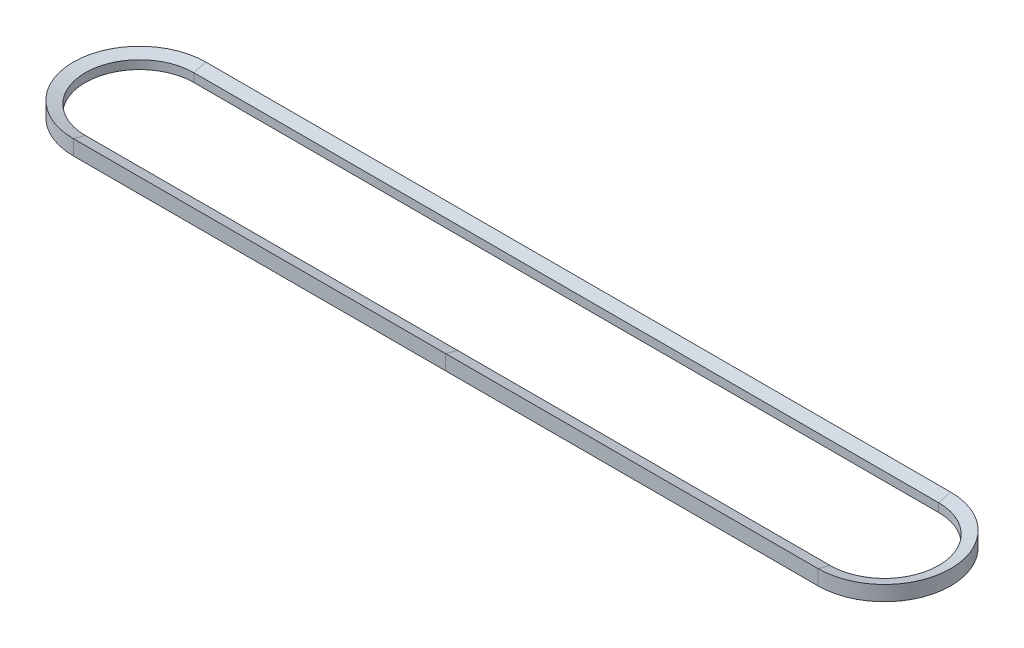
SolidWorks part; units mm, degrees
ref_plane "Front Plane" through (0, 0, 0) normal (0, 0, 1) x (1, 0, 0)
ref_plane "Top Plane" through (0, 0, 0) normal (0, 1, 0) x (1, 0, 0)
ref_plane "Right Plane" through (0, 0, 0) normal (1, 0, 0) x (0, 0, -1)
sketch "Sketch1" plane through (0, 0, 0) normal (0, 1, 0) x (1, 0, 0)
  line L0 (-217.695, 0) -> (217.695, 0) construction
  line L1 (-217.695, 31.75) -> (217.695, 31.75)
  line L2 (-217.695, -31.75) -> (217.695, -31.75)
  arc A0 (-217.695, 31.75) -> (-217.695, -31.75) centre (-217.695, 0) ccw
  arc A1 (217.695, -31.75) -> (217.695, 31.75) centre (217.695, 0) ccw
  point P3 (0, 0)
  dimension "D2" = 31.75
  dimension "D1" = 435.39
sketch "Sketch2" plane through (0, 0, 0) normal (1, 0, 0) x (0, 0, -1)
  line L0 (-38.75, 4.3756) -> (-31.75, 2.5)
  line L1 (-31.75, 2.5) -> (-31.75, -2.5)
  line L2 (-31.75, -2.5) -> (-38.75, -4.3756)
  line L3 (-38.75, -4.3756) -> (-38.75, 4.3756)
  line L4 (31.75, 0) -> (-31.75, 0) construction
  point P6 (-31.75, 0)
  dimension "D1" = 15
  dimension "D2" = 15
  dimension "D3" = 7
  dimension "D4" = 5
sweep "Sweep1" add profiles "Sketch2" path "Sketch1"
